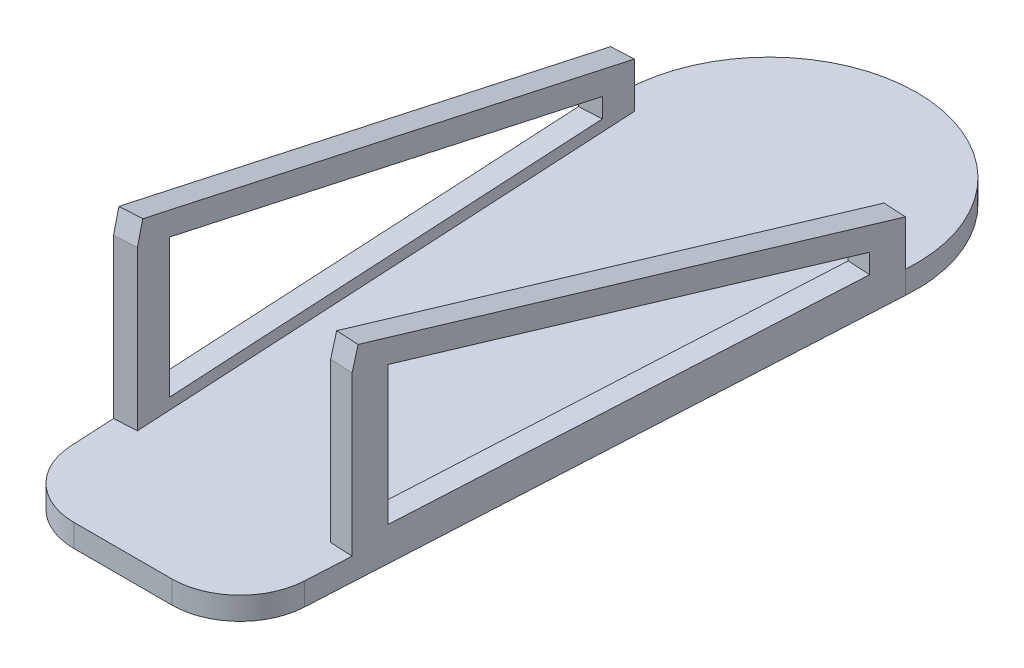
SolidWorks part; units mm, degrees
ref_plane "前视基准面" through (0, 0, 0) normal (0, 0, 1) x (1, 0, 0)
ref_plane "上视基准面" through (0, 0, 0) normal (0, 1, 0) x (1, 0, 0)
ref_plane "右视基准面" through (0, 0, 0) normal (1, 0, 0) x (0, 0, -1)
other "Configuration Table"
sketch "草图1" plane through (0, 0, 0) normal (0, 1, 0) x (1, 0, 0)
  line L0 (-65, 130) -> (-51.5212, -121.6048)
  line L5 (-21.5641, -150) -> (21.5641, -150)
  line L6 (51.5212, -121.6048) -> (65, 130)
  line L7 (0, 0) -> (0, -150) construction
  line L8 (-65, 130) -> (65, 130) construction
  line L9 (0, 0) -> (0, 130) construction
  arc A0 (-65, 130) -> (65, 130) centre (0, 134.8214) cw
  arc A1 (21.5641, -150) -> (51.5212, -121.6048) centre (21.5641, -120) ccw
  arc A2 (-51.5212, -121.6048) -> (-21.5641, -150) centre (-21.5641, -120) ccw
  point P0 (0, 0)
  point P9 (0, 200)
  point P13 (50, -150)
  point P16 (-50, -150)
  dimension "D6" = 30
  dimension "D1" = 150
  dimension "D2" = 130
  dimension "D3" = 70
  dimension "D4" = 130
  dimension "D5" = 100
extrude "凸台-拉伸1" add sketch "草图1" along normal blind 10
sketch "草图2" plane through (57.8696, 0, 3.1002) normal (0.9986, 0, 0.0535) x (0.0535, 0, -0.9986)
  line L1 (-96.114, 89.6779) -> (133.291, 30)
  line L2 (133.291, 30) -> (133.291, 10)
  line L3 (133.291, 10) -> (-98.6317, 10)
  line L4 (-83.6317, 76.0979) -> (118.291, 23.5693)
  line L5 (118.291, 23.5693) -> (118.291, 15)
  line L6 (118.291, 15) -> (-83.6317, 15)
  line L7 (-83.6317, 15) -> (-83.6317, 76.0979)
  line L8 (-98.6317, 10) -> (-98.6317, 80)
  line L11 (-98.6317, 80) -> (-96.114, 89.6779)
  line L12 (-83.6317, 76.0979) -> (-98.6317, 80) construction
  line L13 (-118.6746, 10) -> (133.291, 10) construction
  line L14 (-148.6317, 10) -> (-148.6317, 0) construction
  dimension "D1" = 20
  dimension "D2" = 5
  dimension "D3" = 15
  dimension "D4" = 15
  dimension "D5" = 10
  dimension "D6" = 70
  dimension "D7" = 50
extrude "凸台-拉伸2" add sketch "草图2" against normal blind 10
mirror "镜向1" about plane through (0, 0, 0) normal (1, 0, 0) of "凸台-拉伸2"
